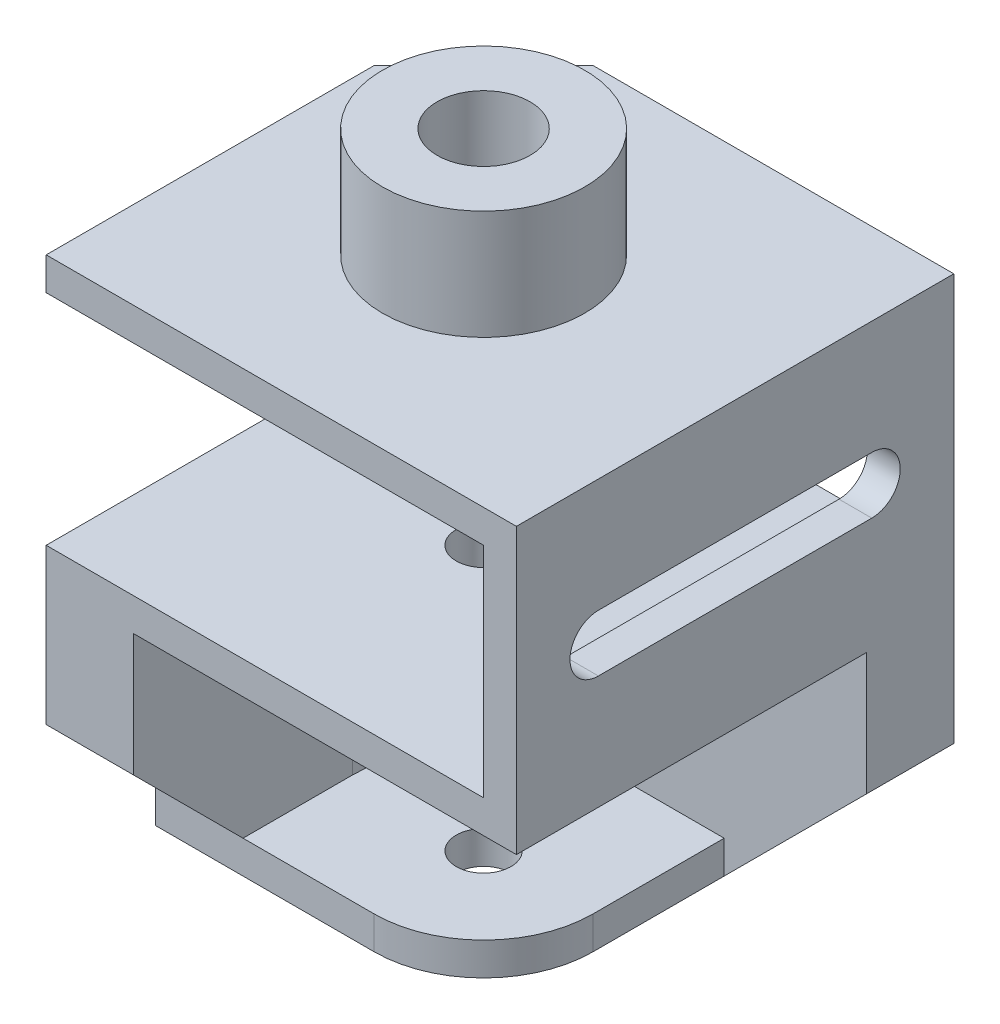
SolidWorks part; units mm, degrees
ref_plane "Front Plane" through (0, 0, 0) normal (0, 0, 1) x (1, 0, 0)
ref_plane "Top Plane" through (0, 0, 0) normal (0, 1, 0) x (1, 0, 0)
ref_plane "Right Plane" through (0, 0, 0) normal (1, 0, 0) x (0, 0, -1)
sketch "Sketch1" plane through (0, 0, 0) normal (0, 1, 0) x (1, 0, 0)
  line L1 (-20, 20) -> (20, 20)
  line L2 (-20, 20) -> (-20, -20)
  line L3 (-20, -20) -> (20, -20)
  line L4 (20, 20) -> (20, -20)
  line L5 (-20, 20) -> (20, -20) construction
  line L6 (-20, -20) -> (20, 20) construction
  circle A0 centre (0, 0) radius 4.25
  point P0 (0, 0)
  dimension "D3" = 8.5
  dimension "D1" = 40
  dimension "D2" = 40
extrude "Boss-Extrude1" add sketch "Sketch1" along normal blind 3
sketch "Sketch2" plane through (0, 3, 0) normal (0, 1, 0) x (1, 0, 0)
  circle A0 centre (0, 0) radius 4.25
  circle A1 centre (0, 0) radius 9.25
  dimension "D1" = 5
extrude "Boss-Extrude2" add sketch "Sketch2" along normal blind 10
sketch "Sketch3" plane through (20, 0, 0) normal (1, 0, 0) x (0, 0, -1)
  line L1 (-20, 3) -> (20, 3)
  line L2 (-20, 3) -> (-20, -20)
  line L3 (-20, -20) -> (20, -20)
  line L4 (20, 3) -> (20, -20)
  dimension "D1" = 23
extrude "Boss-Extrude3" add sketch "Sketch3" along normal blind 3
sketch "Sketch4" plane through (20, 0, 0) normal (-1, 0, 0) x (0, 0, 1)
  line L0 (-20, 0) -> (20, -20) construction
  line L1 (-12.5, -10) -> (12.5, -10) construction
  line L2 (-12.5, -7.4) -> (12.5, -7.4)
  line L3 (-12.5, -12.6) -> (12.5, -12.6)
  arc A0 (-12.5, -7.4) -> (-12.5, -12.6) centre (-12.5, -10) ccw
  arc A1 (12.5, -12.6) -> (12.5, -7.4) centre (12.5, -10) ccw
  point P6 (0, -10)
  dimension "D2" = 2.6
  dimension "D1" = 25
extrude "Cut-Extrude1" cut sketch "Sketch4" against normal blind 3
sketch "Sketch5" plane through (0, -20, 0) normal (0, -1, 0) x (-1, 0, 0)
  line L1 (-23, -20) -> (20, -20)
  line L2 (-23, -20) -> (-23, 20)
  line L3 (-23, 20) -> (20, 20)
  line L4 (20, -20) -> (20, 20)
  dimension "D1" = 40
  dimension "D2" = 43
extrude "Boss-Extrude4" add sketch "Sketch5" along normal blind 3
sketch "Sketch6" plane through (0, -20, 0) normal (0, 1, 0) x (1, 0, 0)
  line L0 (20, -20) -> (-20, 20) construction
  circle A0 centre (0, 0) radius 2.5
  dimension "D1" = 5
extrude "Cut-Extrude2" cut sketch "Sketch6" against normal blind 10
sketch "Sketch7" plane through (0, -23, 0) normal (0, -1, 0) x (-1, 0, 0)
  circle A0 centre (0, 0) radius 2.5
  circle A1 centre (0, 0) radius 6
  dimension "D1" = 12
extrude "Boss-Extrude5" add sketch "Sketch7" along normal blind 1
sketch "Sketch9" plane through (0, -23, 0) normal (0, -1, 0) x (1, 0, 0)
  line L0 (23, -12) -> (0, -12)
  line L1 (23, -20) -> (23, 20) construction
  line L2 (-12, 0) -> (-12, 20)
  line L3 (23, 20) -> (-20, 20) construction
  line L4 (-12, 20) -> (-20, 20)
  line L5 (-20, 20) -> (-20, -10)
  line L6 (-20, 20) -> (-20, -20) construction
  line L7 (-20, -10) -> (-10, -20)
  line L8 (-20, -20) -> (23, -20) construction
  line L9 (-10, -20) -> (23, -20)
  line L10 (23, -20) -> (23, -12)
  arc A0 (0, -12) -> (-12, 0) centre (0, 0) cw
  circle A1 centre (0, 0) radius 9 construction
  circle A2 centre (0, 0) radius 4.5 construction
  point P22 (0, 0)
  dimension "D3" = 3
  dimension "D1" = 10
  dimension "D2" = 10
extrude "Boss-Extrude6" add sketch "Sketch9" along normal up to surface (21.2 mm away)
chamfer "Chamfer2" distance 10 angle 45 2 edges at (23, -44.2, -16) (-16, -44.2, 20)
sketch "Sketch10" plane through (0, -44.2, 0) normal (0, -1, 0) x (1, 0, 0)
  line L0 (0, 10) -> (-12, 10)
  line L1 (10, 0) -> (10, -20)
  line L7 (-10, -20) -> (13, -20)
  line L8 (13, -20) -> (13, -12)
  line L9 (13, -12) -> (0, -12)
  line L10 (-12, 0) -> (-12, 10)
  line L11 (-12, 10) -> (-20, 10)
  line L12 (-20, 10) -> (-20, -10)
  line L13 (-20, -10) -> (-10, -20)
  line L14 (-10, -20) -> (10, -20)
  line L18 (-12, 10) -> (-20, 10)
  line L19 (-20, 10) -> (-20, -10)
  line L20 (-20, -10) -> (-10, -20)
  arc A1 (-12, 0) -> (0, -12) centre (0, 0) ccw
  circle A2 centre (0, 0) radius 2.5
  arc A3 (10, 0) -> (0, 10) centre (0, 0) ccw
  dimension "D1" = 0
extrude "Boss-Extrude7" add sketch "Sketch10" along normal blind 3
sketch "Sketch11" plane through (0, -23, 0) normal (0, -1, 0) x (1, 0, 0)
  line L3 (-10, -20) -> (-20, -10)
  line L4 (-20, -10) -> (-20, -20)
  line L5 (-20, -20) -> (-10, -20)
  line L6 (-10, -20) -> (-20, -10)
  line L7 (-20, -10) -> (-20, -20)
  line L8 (-20, -20) -> (-10, -20)
  dimension "D1" = 0
extrude "Cut-Extrude3" cut sketch "Sketch11" against normal blind 31
sketch "Sketch12" plane through (0, 0, -20) normal (0, 0, -1) x (-1, 0, 0)
  line L0 (-10, -47.2) -> (-13, -44.2)
  line L1 (-13, -44.2) -> (-10, -44.2)
  line L2 (-10, -44.2) -> (-10, -47.2)
extrude "Boss-Extrude8" add sketch "Sketch12" against normal blind 8
